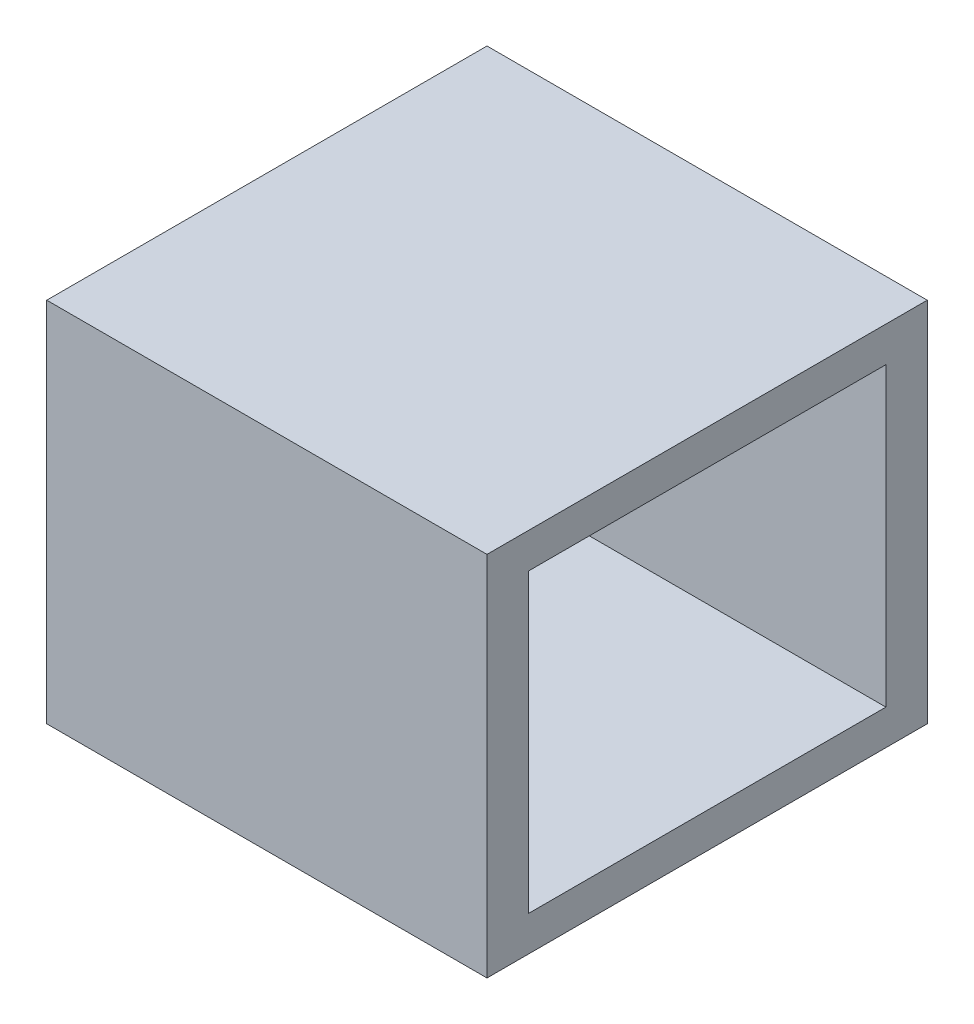
SolidWorks part; units mm, degrees
ref_plane "Front Plane" through (0, 0, 0) normal (0, 0, 1) x (1, 0, 0)
ref_plane "Top Plane" through (0, 0, 0) normal (0, 1, 0) x (1, 0, 0)
ref_plane "Right Plane" through (0, 0, 0) normal (1, 0, 0) x (0, 0, -1)
sketch "Sketch1" plane through (0, 0, 0) normal (0, 0, 1) x (1, 0, 0)
  line L1 (-76.2, -63.5) -> (76.2, -63.5)
  line L2 (-76.2, -63.5) -> (-76.2, 63.5)
  line L3 (-76.2, 63.5) -> (76.2, 63.5)
  line L4 (76.2, -63.5) -> (76.2, 63.5)
  line L5 (-76.2, -63.5) -> (76.2, 63.5) construction
  line L6 (-76.2, 63.5) -> (76.2, -63.5) construction
  point P0 (0, 0)
  dimension "D1" = 152.4
  dimension "D2" = 127
extrude "Boss-Extrude1" add sketch "Sketch1" along normal mid plane 152.4
sketch "Sketch2" plane through (0, 0, 76.2) normal (0, 0, 1) x (1, 0, 0)
  line L1 (0, 50.5506) -> (-43.7781, -25.2753)
  line L2 (-43.7781, -25.2753) -> (43.7781, -25.2753)
  line L3 (43.7781, -25.2753) -> (0, 50.5506)
  circle A0 centre (0, 0) radius 25.2753 construction
extrude "Cut-Extrude1" [suppressed] cut sketch "Sketch2" against normal through all
sketch "Sketch3" plane through (76.2, 0, 0) normal (1, 0, 0) x (0, 0, -1)
  line L1 (-61.8845, -51.332) -> (61.8845, -51.332)
  line L2 (-61.8845, -51.332) -> (-61.8845, 51.332)
  line L3 (-61.8845, 51.332) -> (61.8845, 51.332)
  line L4 (61.8845, -51.332) -> (61.8845, 51.332)
  line L5 (-61.8845, -51.332) -> (61.8845, 51.332) construction
  line L6 (-61.8845, 51.332) -> (61.8845, -51.332) construction
  point P0 (0, 0)
extrude "Cut-Extrude2" cut sketch "Sketch3" against normal through all
sketch "Sketch4" plane through (0, 63.5, 0) normal (0, 1, 0) x (1, 0, 0)
  circle A0 centre (0, 0) radius 46.9609
extrude "Cut-Extrude3" [suppressed] cut sketch "Sketch4" against normal through all
